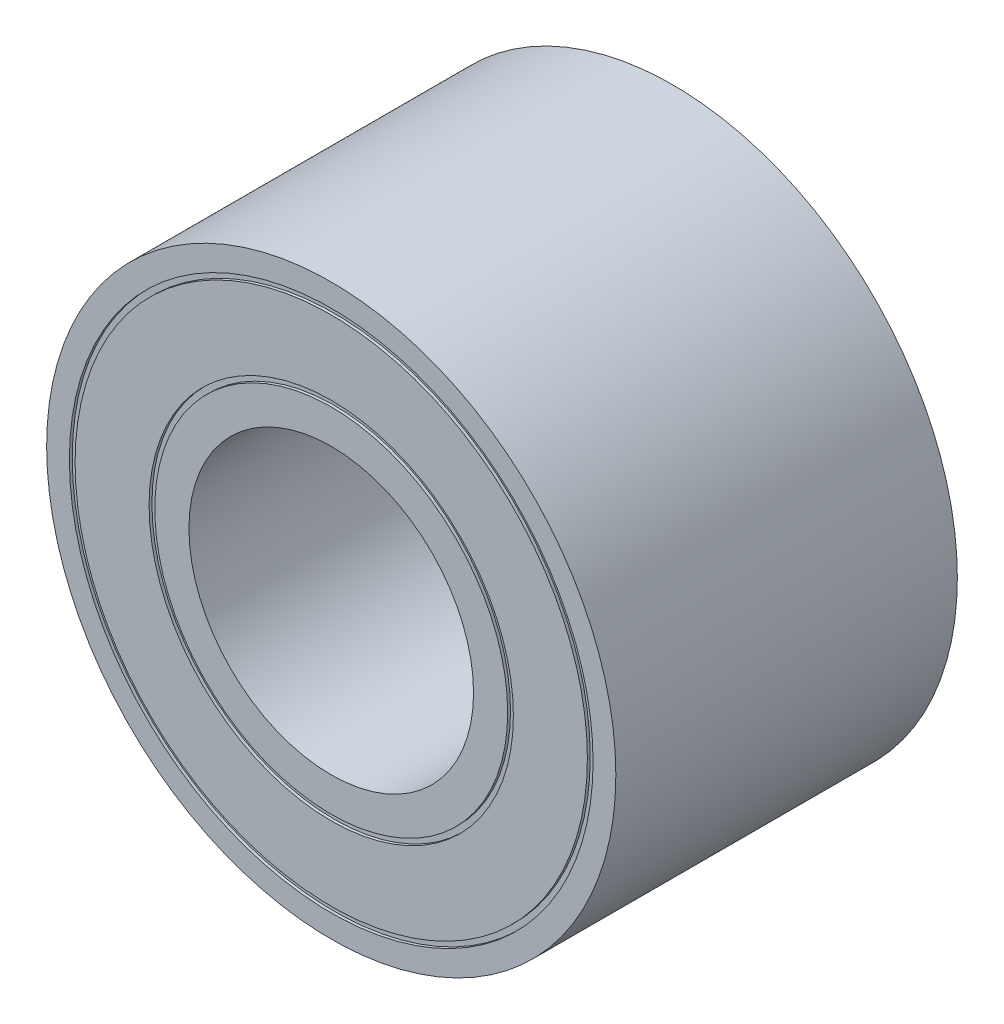
SolidWorks part; units mm, degrees
material "ASTM A36 Aço"
ref_plane "Plano frontal" through (0, 0, 0) normal (0, 0, 1) x (1, 0, 0)
ref_plane "Plano superior" through (0, 0, 0) normal (0, 1, 0) x (1, 0, 0)
ref_plane "Plano direito" through (0, 0, 0) normal (1, 0, 0) x (0, 0, -1)
sketch "Esboço1" plane through (0, 0, 0) normal (0, 0, 1) x (1, 0, 0)
  circle A0 centre (0, 0) radius 12.5
  circle A1 centre (0, 0) radius 25
  dimension "D1" = 25
  dimension "D2" = 50
extrude "Ressalto-extrusão1" add sketch "Esboço1" along normal mid plane 30
sketch "Esboço2" plane through (0, 0, 15) normal (0, 0, 1) x (1, 0, 0)
  circle A0 centre (0, 0) radius 23
  circle A1 centre (0, 0) radius 25
  circle A2 centre (0, 0) radius 25
  circle A3 centre (0, 0) radius 22.5
  circle A4 centre (0, 0) radius 16
  circle A5 centre (0, 0) radius 15.5
  circle A6 centre (0, 0) radius 15.5
  dimension "D1" = 0
  dimension "D2" = 3
  dimension "D3" = 0.5
  dimension "D4" = 2
  dimension "D5" = 0.5
extrude "Corte-extrusão1" cut sketch "Esboço2" against normal blind 0.25 contours A4 A6 | A0 A3
mirror "Espelhar1" about plane through (0, 0, 0) normal (0, 0, 1) of "Corte-extrusão1"
